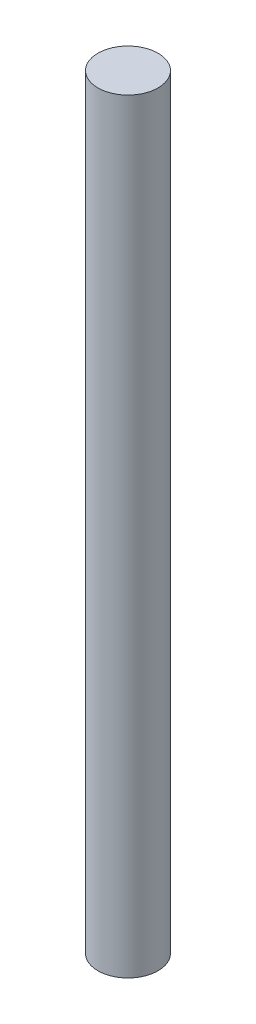
SolidWorks part; units mm, degrees
ref_plane "Front Plane" through (0, 0, 0) normal (0, 0, 1) x (1, 0, 0)
ref_plane "Top Plane" through (0, 0, 0) normal (0, 1, 0) x (1, 0, 0)
ref_plane "Right Plane" through (0, 0, 0) normal (1, 0, 0) x (0, 0, -1)
sketch "Sketch1" plane through (0, 0, 0) normal (0, 1, 0) x (1, 0, 0)
  circle A0 centre (0, 0) radius 3.995
  dimension "D1" = 7.99
extrude "Boss-Extrude1" add sketch "Sketch1" along normal blind 101.6
